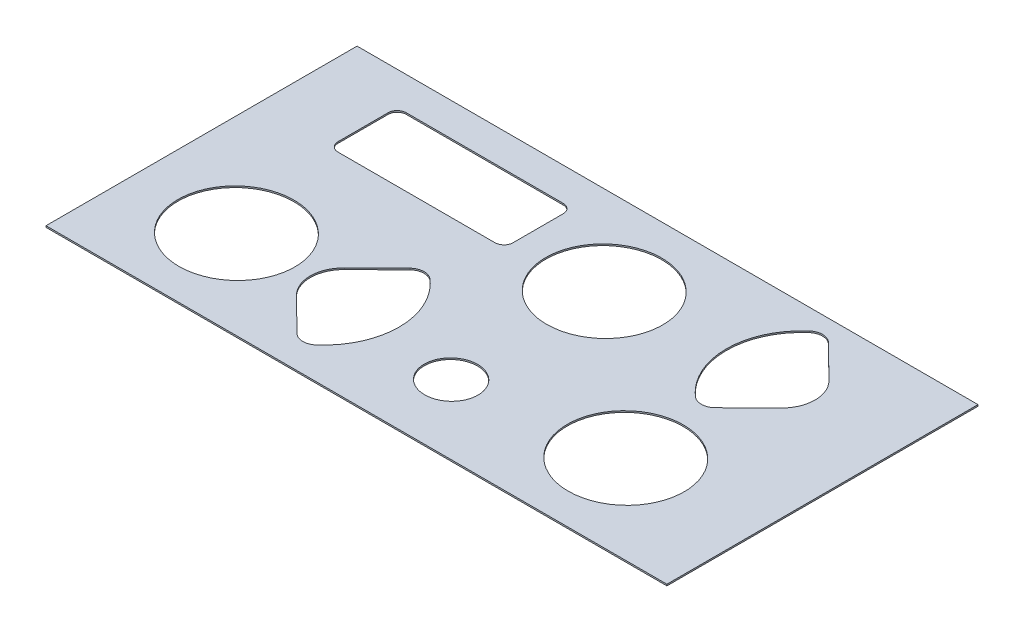
SolidWorks part; units mm, degrees
ref_plane "Front Plane" through (0, 0, 0) normal (0, 0, 1) x (1, 0, 0)
ref_plane "Top Plane" through (0, 0, 0) normal (0, 1, 0) x (1, 0, 0)
ref_plane "Right Plane" through (0, 0, 0) normal (1, 0, 0) x (0, 0, -1)
sketch "Sketch1" plane through (0, 0, 0) normal (0, 1, 0) x (1, 0, 0)
  line L0 (61.2611, -62.6261) -> (61.2611, -0.2)
  line L1 (-61.2611, -62.6261) -> (-61.2611, -0.2)
  line L2 (0, -62.8261) -> (30.6305, -62.8261) construction
  line L3 (61.2611, 0) -> (-61.2611, 0) construction
  line L4 (30.6305, -62.8261) -> (61.2611, -62.8261) construction
  line L6 (-30.6305, -62.8261) -> (0, -62.8261) construction
  line L7 (30.6305, -62.8261) -> (30.6305, -44.8261) construction
  line L8 (5.0083, 0) -> (5.0083, -18) construction
  line L9 (5.0083, -18) -> (5.0083, 0) construction
  line L10 (-61.2611, -62.8261) -> (61.2611, -62.8261) construction
  line L16 (-46.0131, -8.6415) -> (-46.0131, -18.7352) construction
  line L18 (-45.0131, -7.6415) -> (-14.0739, -7.6415) construction
  line L19 (-17.5248, -34.0562) -> (-24.0521, -40.5834) construction
  line L20 (-45.0131, -19.7352) -> (-14.0739, -19.7352) construction
  line L23 (-13.0739, -8.6415) -> (-13.0739, -18.7352) construction
  line L24 (-16.8177, -34.7633) -> (-23.345, -41.2906) construction
  line L25 (-17.5279, -55.593) -> (-24.0521, -49.0687) construction
  line L26 (-16.8208, -54.8859) -> (-23.345, -48.3616) construction
  line L27 (34.6223, -25.8138) -> (41.1465, -19.2896) construction
  line L28 (34.6192, -5.6912) -> (41.1465, -12.2185) construction
  line L29 (35.3294, -26.5209) -> (41.8536, -19.9967) construction
  line L30 (35.3263, -4.9841) -> (41.8536, -11.5114) construction
  line L35 (-46.8131, -8.6415) -> (-46.8131, -18.7352)
  line L36 (-45.0131, -20.5352) -> (-14.0739, -20.5352)
  line L37 (-12.2739, -8.6415) -> (-12.2739, -18.7352)
  line L38 (-45.0131, -6.8415) -> (-14.0739, -6.8415)
  line L39 (35.892, -4.4184) -> (42.4193, -10.9457)
  line L40 (35.8951, -27.0866) -> (42.4193, -20.5624)
  line L41 (-18.0936, -56.1587) -> (-24.6178, -49.6344)
  line L42 (-18.0905, -33.4905) -> (-24.6178, -40.0178)
  line L44 (61.2611, -0.2) -> (-61.2611, -0.2)
  line L46 (-61.2611, -62.6261) -> (61.2611, -62.6261)
  line L47 (61.0611, -0.2) -> (-61.0611, -0.2) construction
  line L48 (-61.0611, -62.6261) -> (-61.0611, -0.2) construction
  line L49 (-61.0611, -62.6261) -> (61.0611, -62.6261) construction
  line L50 (-61.2611, -62.8261) -> (-61.2611, 0) construction
  line L51 (61.0611, -62.6261) -> (61.0611, -0.2) construction
  line L52 (61.2611, -62.8261) -> (61.2611, 0) construction
  circle A2 centre (5.0083, -18) radius 10.738 construction
  circle A7 centre (35.6388, -44.8261) radius 10.738 construction
  circle A8 centre (5.0083, -18) radius 10.738 construction
  arc A12 (-14.0739, -7.6415) -> (-13.0739, -8.6415) centre (-14.0739, -8.6415) cw construction
  arc A14 (-14.0739, -19.7352) -> (-13.0739, -18.7352) centre (-14.0739, -18.7352) ccw construction
  arc A16 (-45.0131, -19.7352) -> (-46.0131, -18.7352) centre (-45.0131, -18.7352) cw construction
  arc A17 (-45.0131, -7.6415) -> (-46.0131, -8.6415) centre (-45.0131, -8.6415) ccw construction
  arc A18 (-16.8177, -34.7633) -> (-15.4481, -34.7213) centre (-16.1106, -35.4704) cw construction
  arc A19 (-16.8208, -54.8859) -> (-15.4541, -54.9281) centre (-16.115, -54.1801) ccw construction
  arc A24 (-24.0521, -40.5834) -> (-24.0521, -49.0687) centre (-19.8095, -44.8261) ccw construction
  arc A25 (-17.5279, -55.593) -> (-14.792, -55.6775) centre (-16.115, -54.1801) ccw construction
  arc A26 (-14.7856, -33.9723) -> (-14.792, -55.6775) centre (-24.3824, -44.8221) cw construction
  arc A27 (-15.4481, -34.7213) -> (-15.4541, -54.9281) centre (-24.3824, -44.8221) cw construction
  arc A28 (-17.5248, -34.0562) -> (-14.7856, -33.9723) centre (-16.1106, -35.4704) cw construction
  arc A29 (-23.345, -41.2906) -> (-23.345, -48.3616) centre (-19.8095, -44.8261) ccw construction
  circle A30 centre (-41.1926, -44.8221) radius 10.738 construction
  arc A31 (34.6192, -5.6912) -> (33.2496, -5.6493) centre (33.9121, -6.3983) ccw construction
  arc A32 (41.1465, -12.2185) -> (41.1465, -19.2896) centre (37.611, -15.7541) cw construction
  arc A33 (33.2496, -5.6493) -> (33.2556, -25.8561) centre (42.1839, -15.75) ccw construction
  arc A34 (34.6223, -25.8138) -> (33.2556, -25.8561) centre (33.9165, -25.1081) cw construction
  arc A35 (35.3294, -26.5209) -> (32.5935, -26.6055) centre (33.9165, -25.1081) cw construction
  arc A36 (32.5871, -4.9003) -> (32.5935, -26.6055) centre (42.1839, -15.75) ccw construction
  arc A37 (41.8536, -11.5114) -> (41.8536, -19.9967) centre (37.611, -15.7541) cw construction
  arc A38 (35.3263, -4.9841) -> (32.5871, -4.9003) centre (33.9121, -6.3983) ccw construction
  circle A41 centre (5.0082, -48.7173) radius 4.5 construction
  circle A42 centre (-41.1926, -44.8221) radius 11.538
  arc A43 (-45.0131, -20.5352) -> (-46.8131, -18.7352) centre (-45.0131, -18.7352) cw
  arc A44 (-14.0739, -20.5352) -> (-12.2739, -18.7352) centre (-14.0739, -18.7352) ccw
  arc A45 (-14.0739, -6.8415) -> (-12.2739, -8.6415) centre (-14.0739, -8.6415) cw
  arc A46 (-45.0131, -6.8415) -> (-46.8131, -8.6415) centre (-45.0131, -8.6415) ccw
  circle A47 centre (5.0083, -18) radius 11.538
  circle A48 centre (5.0082, -48.7173) radius 5.3
  circle A49 centre (35.6388, -44.8261) radius 11.538
  arc A50 (35.8951, -27.0866) -> (32.0639, -27.2051) centre (33.9165, -25.1081) cw
  arc A51 (32.057, -4.301) -> (32.0639, -27.2051) centre (42.1839, -15.75) ccw
  arc A52 (35.892, -4.4184) -> (32.057, -4.301) centre (33.9121, -6.3983) ccw
  arc A53 (42.4193, -10.9457) -> (42.4193, -20.5624) centre (37.611, -15.7541) cw
  arc A54 (-14.2555, -33.3731) -> (-14.2624, -56.2771) centre (-24.3824, -44.8221) cw
  arc A55 (-18.0936, -56.1587) -> (-14.2624, -56.2771) centre (-16.115, -54.1801) ccw
  arc A56 (-24.6178, -40.0178) -> (-24.6178, -49.6344) centre (-19.8095, -44.8261) ccw
  arc A57 (-18.0905, -33.4905) -> (-14.2555, -33.3731) centre (-16.1106, -35.4704) cw
  dimension "D5" = 1
  dimension "D6" = 0.2
  dimension "D8" = 9
  dimension "D1" = 0.8
  dimension "D2" = 18
  dimension "D3" = 30.6305
  dimension "D4" = 18
extrude "Boss-Extrude1" add sketch "Sketch1" along normal blind 0.3
scale "Scale1" scale about centroid uniform scaling no x scale factor 1.017 y scale factor 1 z scale factor 1
